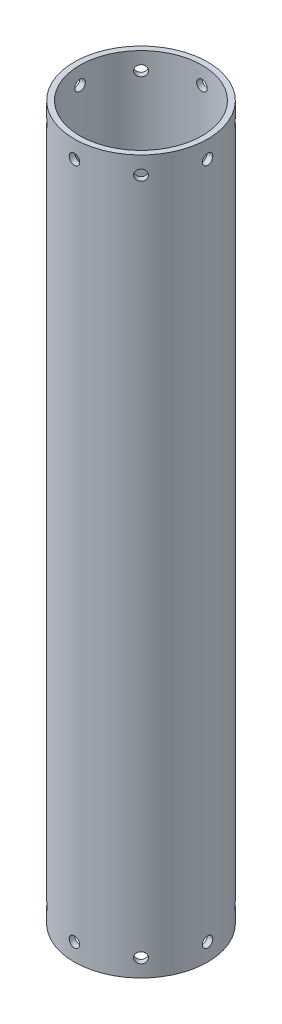
SolidWorks part; units mm, degrees
ref_plane "Plano frontal" through (0, 0, 0) normal (0, 0, 1) x (1, 0, 0)
ref_plane "Plano superior" through (0, 0, 0) normal (0, 1, 0) x (1, 0, 0)
ref_plane "Plano direito" through (0, 0, 0) normal (1, 0, 0) x (0, 0, -1)
sketch "Esboço1" plane through (0, 0, 0) normal (0, 1, 0) x (1, 0, 0)
  circle A0 centre (0, 0) radius 38.1
  circle A1 centre (0, 0) radius 34.925
  dimension "D1" = 76.2
  dimension "D2" = 3.175
extrude "Ressalto-extrusão1" add sketch "Esboço1" along normal blind 407
ref_plane "Plano1" through (38.1, 0, 0) normal (1, 0, 0) x (0, 0, -1)
sketch "Esboço2" plane through (38.1, 0, 0) normal (1, 0, 0) x (0, 0, -1)
  line L0 (0, 400) -> (0, 416.9684) construction
  line L2 (34.925, 407) -> (-34.925, 407) construction
  circle A0 centre (0, 397) radius 3
  circle A1 centre (0, 10) radius 3
  dimension "D1" = 6
  dimension "D3" = 6
  dimension "D2" = 10
  dimension "D4" = 10
extrude "Corte-extrusão1" cut sketch "Esboço2" against normal up to next
pattern_circular "PadrãoCircular1" count 8 over 360 about axis through (0, 407, 0) along (0, 1, 0) of "Corte-extrusão1"
